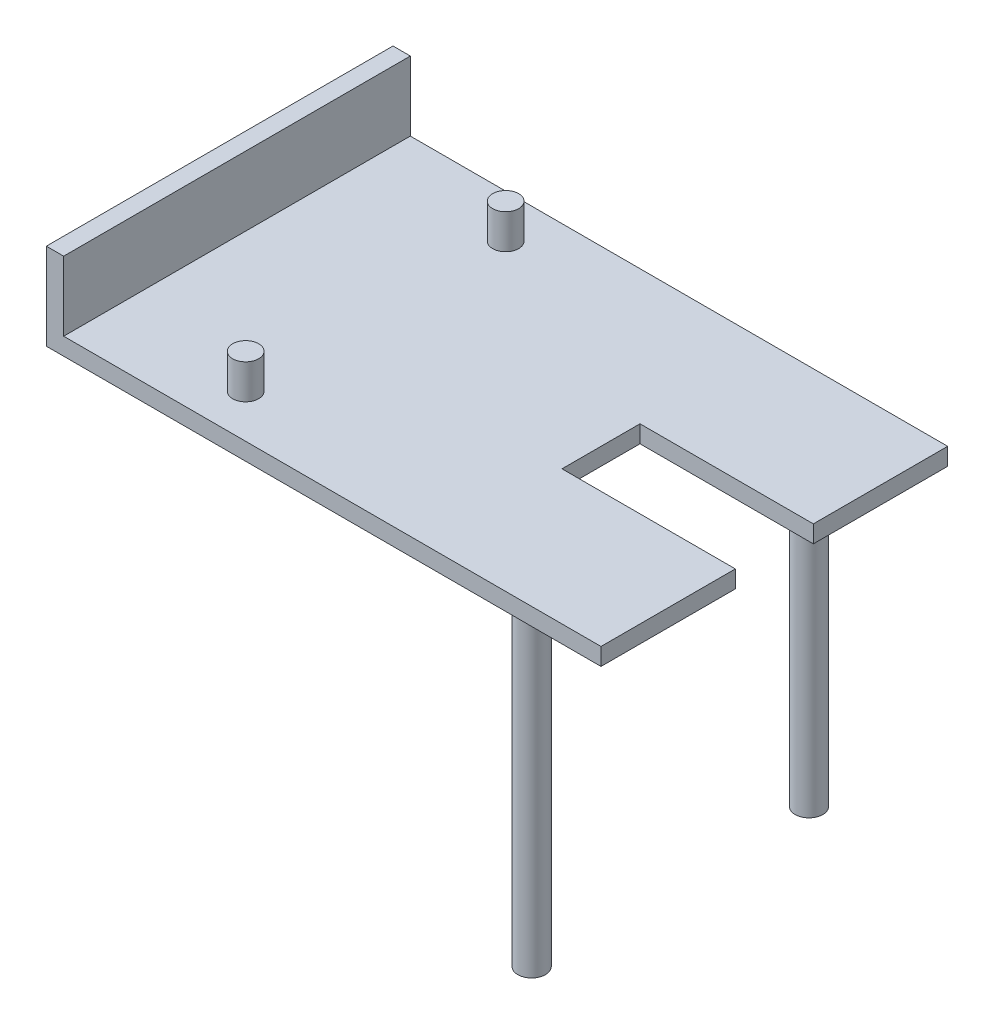
SolidWorks part; units mm, degrees
ref_plane "Plan de face" through (0, 0, 0) normal (0, 0, 1) x (1, 0, 0)
ref_plane "Plan de dessus" through (0, 0, 0) normal (0, 1, 0) x (1, 0, 0)
ref_plane "Plan de droite" through (0, 0, 0) normal (1, 0, 0) x (0, 0, -1)
sketch "Esquisse1" plane through (0, 0, 0) normal (0, 0, 1) x (1, 0, 0)
  line L1 (0, 0) -> (320, 0)
  line L2 (0, 0) -> (0, 10)
  line L3 (0, 10) -> (320, 10)
  line L4 (320, 0) -> (320, 10)
  line L5 (0, 0) -> (10, 0)
  line L6 (0, 0) -> (0, 50)
  line L7 (0, 50) -> (10, 50)
  line L8 (10, 0) -> (10, 50)
  dimension "D1" = 10
  dimension "D2" = 50
  dimension "D3" = 320
extrude "Boss.-Extru.1" add sketch "Esquisse1" along normal blind 200 contours L8 L1 L4 L3 | L3 L8 L7 L6 | L1 L8 L3 L2
sketch "Esquisse2" plane through (0, 10, 0) normal (0, 1, 0) x (1, 0, 0)
  line L0 (10, -200) -> (10, 0) construction
  line L1 (10, -100) -> (320, -100) construction
  line L2 (10, -200) -> (10, 0) construction
  line L3 (320, -200) -> (320, 0) construction
  line L4 (90, -25) -> (90, -175) construction
  circle A0 centre (90, -25) radius 7.5
  circle A1 centre (90, -175) radius 7.5
  point P6 (90, -100)
  dimension "D1" = 80
  dimension "D2" = 150
  dimension "D3" = 15
extrude "Boss.-Extru.2" add sketch "Esquisse2" along normal blind 20
sketch "Esquisse3" plane through (0, 10, 0) normal (0, 1, 0) x (1, 0, 0)
  line L0 (260, -20) -> (260, -180) construction
  line L1 (10, -100) -> (320, -100) construction
  line L2 (10, -200) -> (10, 0) construction
  line L3 (320, -200) -> (320, 0) construction
  circle A0 centre (260, -20) radius 8
  circle A1 centre (260, -180) radius 8
  point P10 (260, -100)
  dimension "D1" = 16
  dimension "D2" = 160
  dimension "D3" = 60
extrude "Boss.-Extru.3" add sketch "Esquisse3" against normal blind 200
sketch "Esquisse4" plane through (0, 10, 0) normal (0, 1, 0) x (1, 0, 0)
  line L0 (320, -200) -> (320, 0) construction
  line L1 (320, -77.5) -> (220, -77.5)
  line L2 (320, -77.5) -> (320, -122.5)
  line L3 (320, -122.5) -> (220, -122.5)
  line L4 (220, -77.5) -> (220, -122.5)
  line L5 (10, -100) -> (320, -100) construction
  line L6 (10, -200) -> (10, 0) construction
  point P10 (220, -100)
  dimension "D1" = 45
  dimension "D2" = 100
extrude "Enlèv. mat.-Extru.1" cut sketch "Esquisse4" against normal blind 10
